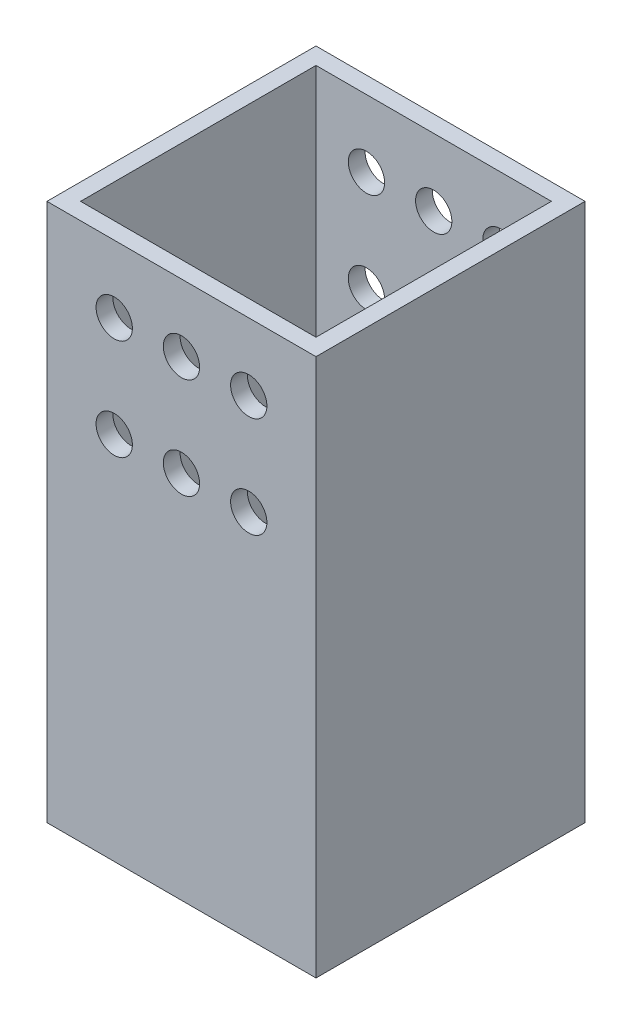
SolidWorks part; units mm, degrees
ref_plane "Front Plane" through (0, 0, 0) normal (0, 0, 1) x (1, 0, 0)
ref_plane "Top Plane" through (0, 0, 0) normal (0, 1, 0) x (1, 0, 0)
ref_plane "Right Plane" through (0, 0, 0) normal (1, 0, 0) x (0, 0, -1)
sketch "Sketch1" plane through (0, 0, 0) normal (0, 1, 0) x (1, 0, 0)
  line L5 (-25.4, -25.4) -> (25.4, -25.4)
  line L6 (-25.4, -25.4) -> (-25.4, 25.4)
  line L7 (-25.4, 25.4) -> (25.4, 25.4)
  line L8 (25.4, -25.4) -> (25.4, 25.4)
  line L9 (-25.4, -25.4) -> (25.4, 25.4) construction
  line L10 (-25.4, 25.4) -> (25.4, -25.4) construction
  line L11 (-22.225, -22.225) -> (22.225, -22.225)
  line L12 (-22.225, -22.225) -> (-22.225, 22.225)
  line L13 (-22.225, 22.225) -> (22.225, 22.225)
  line L14 (22.225, -22.225) -> (22.225, 22.225)
  line L15 (-22.225, -22.225) -> (22.225, 22.225) construction
  line L16 (-22.225, 22.225) -> (22.225, -22.225) construction
  point P0 (0, 0)
  point P6 (0, 0)
  dimension "D1" = 50.8
  dimension "D2" = 50.8
  dimension "D3" = 3.175
  dimension "D4" = 3.175
extrude "Boss-Extrude1" add sketch "Sketch1" along normal blind 101.6
sketch "Sketch2" plane through (0, 0, 25.4) normal (0, 0, 1) x (1, 0, 0)
  line L0 (-25.4, 101.6) -> (-25.4, 0) construction
  line L1 (-25.4, 0) -> (25.4, 0) construction
  circle A0 centre (-12.7, 69.85) radius 3.429
  dimension "D1" = 6.858
  dimension "D2" = 12.7
  dimension "D3" = 69.85
extrude "Cut-Extrude1" cut sketch "Sketch2" against normal blind 101.6
pattern_linear "LPattern1" count 3 spacing 12.7 along (1, 0, 0) count 2 spacing 19.05 along (0, 1, 0) of "Cut-Extrude1"
